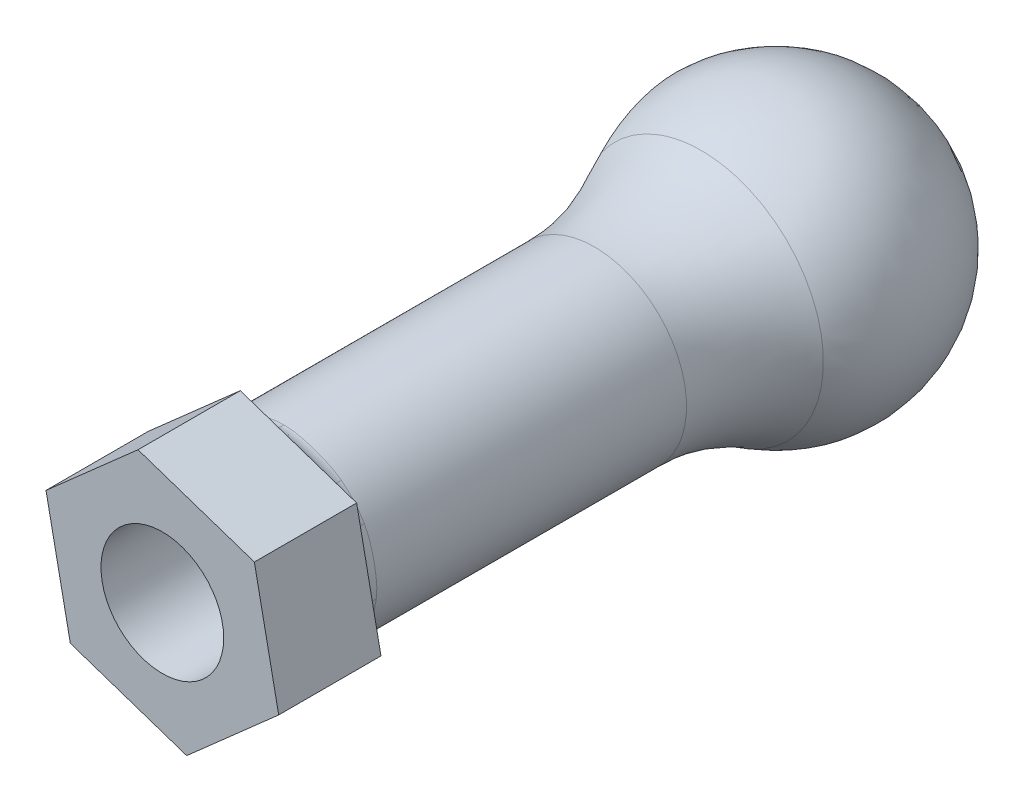
SolidWorks part; units mm, degrees
ref_plane "Front Plane" through (0, 0, 0) normal (0, 0, 1) x (1, 0, 0)
ref_plane "Top Plane" through (0, 0, 0) normal (0, 1, 0) x (1, 0, 0)
ref_plane "Right Plane" through (0, 0, 0) normal (1, 0, 0) x (0, 0, -1)
sketch "Sketch1" plane through (0, 0, 0) normal (0, 0, 1) x (1, 0, 0)
  line L0 (0, 7) -> (0, -7)
  arc A0 (0, -7) -> (0, 7) centre (0, 0) ccw
revolve "Revolve1" add sketch "Sketch1" angle 360 about L0
sketch "Sketch2" plane through (0, 0, 0) normal (0, 0, 1) x (1, 0, 0)
  circle A0 centre (0, 0) radius 4.5
extrude "Boss-Extrude1" add sketch "Sketch2" along normal blind 25
sketch "Sketch3" plane through (0, 0, 25) normal (0, 0, 1) x (1, 0, 0)
  line L1 (5.6877, -1.9105) -> (4.4984, 3.9705)
  line L2 (4.4984, 3.9705) -> (-1.1894, 5.8809)
  line L3 (-1.1894, 5.8809) -> (-5.6877, 1.9105)
  line L4 (-5.6877, 1.9105) -> (-4.4984, -3.9705)
  line L5 (-4.4984, -3.9705) -> (1.1894, -5.8809)
  line L6 (1.1894, -5.8809) -> (5.6877, -1.9105)
  circle A0 centre (0, 0) radius 5.1962 construction
  dimension "D1" = 6
extrude "Boss-Extrude2" add sketch "Sketch3" along normal blind 5
sketch "Sketch4" plane through (0, 0, 30) normal (0, 0, 1) x (1, 0, 0)
  circle A0 centre (0, 0) radius 3
extrude "Cut-Extrude1" cut sketch "Sketch4" against normal blind 20
fillet "Fillet1" radius 10 1 edges at (-4.5, 0, 5.3619)
fillet "Fillet3" radius 1 1 edges at (4.5, 0, 25)
sketch "Sketch5" plane through (0, 0, 0) normal (1, 0, 0) x (0, 0, -1)
  line L0 (6, 0) -> (-6, 0)
  arc A0 (-6, 0) -> (6, 0) centre (0, 0) ccw
  dimension "D1" = 12
revolve "Cut-Revolve1" cut sketch "Sketch5" angle 360 about L0
sketch "Sketch6" plane through (0, 0, 0) normal (1, 0, 0) x (0, 0, -1)
  circle A0 centre (0, 0) radius 5
  dimension "D1" = 10
extrude "Cut-Extrude2" cut sketch "Sketch6" against normal blind 20
